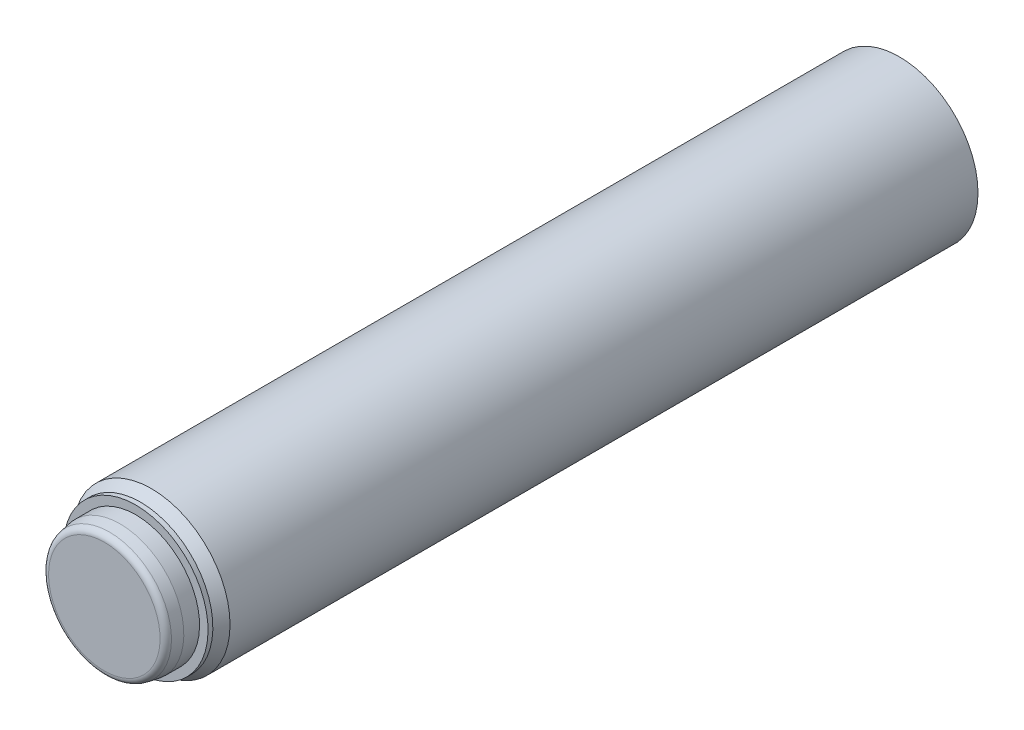
SolidWorks part; units mm, degrees
ref_plane "Alzado" through (0, 0, 0) normal (0, 0, 1) x (1, 0, 0)
ref_plane "Planta" through (0, 0, 0) normal (0, 1, 0) x (1, 0, 0)
ref_plane "Vista lateral" through (0, 0, 0) normal (1, 0, 0) x (0, 0, -1)
sketch "Croquis1" plane through (0, 0, 0) normal (0, 0, 1) x (1, 0, 0)
  circle A0 centre (0, 0) radius 12.5
  dimension "D1" = 25
extrude "Saliente-Extruir1" add sketch "Croquis1" along normal blind 119
sketch "Croquis4" plane through (0, 0, 0) normal (1, 0, 0) x (0, 0, -1)
  line L0 (-119, 0) -> (-126.5, 0)
  line L1 (-119, 12.5) -> (-119, -12.5) construction
  line L2 (-126.5, 0) -> (-126.5, -8.8701)
  line L3 (-125.6736, -9.8549) -> (-124, -10.15)
  line L4 (-124, -10.15) -> (-121.5, -10.15)
  line L5 (-121.5, -10.15) -> (-121.5, -11.5)
  line L6 (-119, 0) -> (-119, -12.5)
  line L7 (-121.5, -11.5) -> (-120.7321, -11.5)
  line L8 (-120.7321, -11.5) -> (-119, -12.5)
  arc A0 (-126.5, -8.8701) -> (-125.6736, -9.8549) centre (-125.5, -8.8701) ccw
  dimension "D9" = 1
  dimension "D1" = 7.5
  dimension "D2" = 10.15
  dimension "D3" = 10
  dimension "D4" = 2.5
  dimension "D5" = 11.5
  dimension "D6" = 60
  dimension "D7" = 12.5
  dimension "D8" = 2.5
revolve "Revolución1" add sketch "Croquis4" angle 360 about L0
sketch "Croquis5" plane through (0, 0, 0) normal (0, 0, -1) x (-1, 0, 0)
  circle A0 centre (0, 0) radius 6
  dimension "D1" = 12
extrude "Cortar-Extruir1" cut sketch "Croquis5" against normal blind 30
